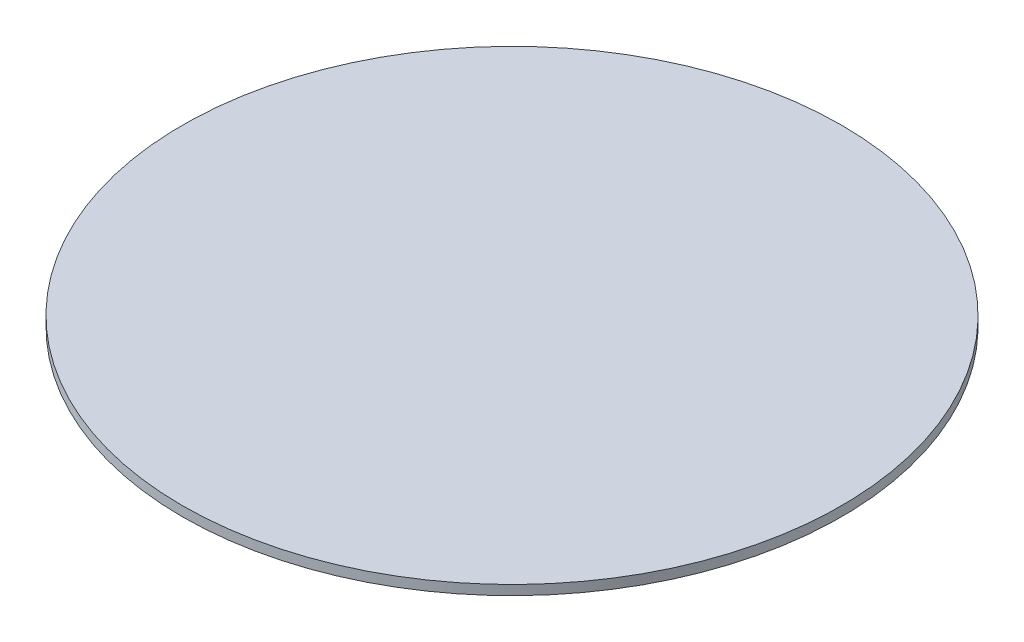
SolidWorks part; units mm, degrees
ref_plane "Front" through (0, 0, 0) normal (0, 0, 1) x (1, 0, 0)
ref_plane "Top" through (0, 0, 0) normal (0, 1, 0) x (1, 0, 0)
ref_plane "Right" through (0, 0, 0) normal (1, 0, 0) x (0, 0, -1)
sketch "Sketch1" plane through (0, 0, 0) normal (0, 1, 0) x (1, 0, 0)
  circle A0 centre (0, 0) radius 19.1
  dimension "D1" = 38.2
extrude "Boss-Extrude1" add sketch "Sketch1" along normal blind 0.5605
